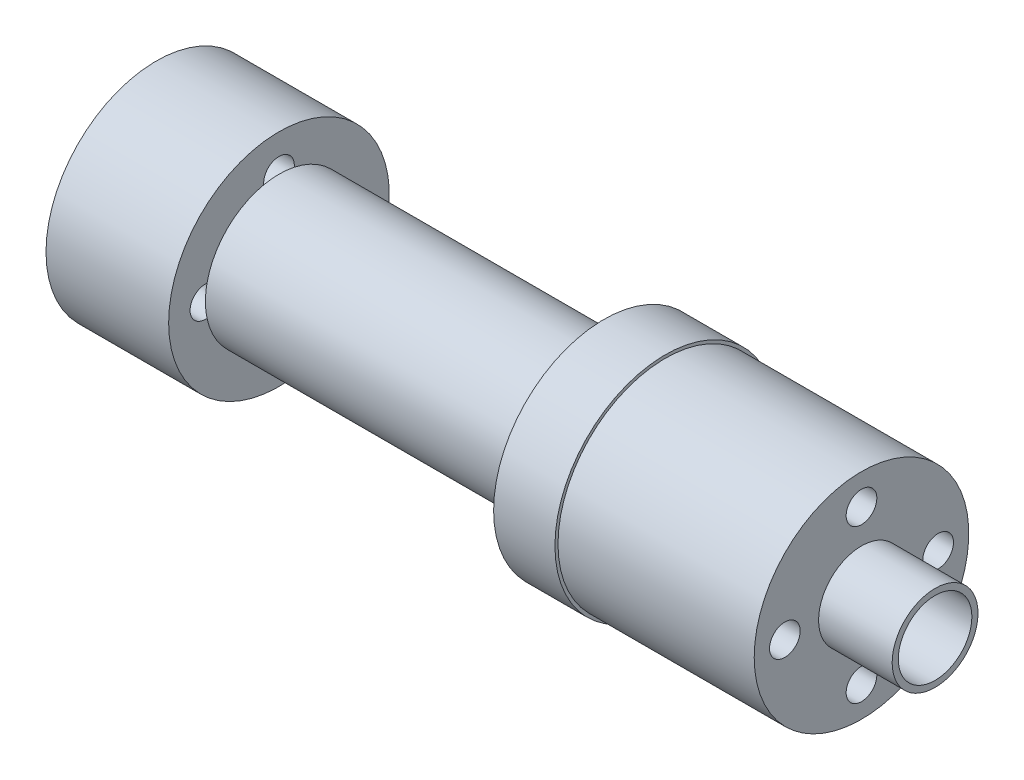
SolidWorks part; units mm, degrees
material "6061 合金"
ref_plane "前视基准面" through (0, 0, 0) normal (0, 0, 1) x (1, 0, 0)
ref_plane "上视基准面" through (0, 0, 0) normal (0, 1, 0) x (1, 0, 0)
ref_plane "右视基准面" through (0, 0, 0) normal (1, 0, 0) x (0, 0, -1)
sketch "草图1" plane through (0, 0, 0) normal (0, 0, 1) x (1, 0, 0)
  line L0 (0, 0) -> (40.4728, 0) construction
  line L1 (0, 9) -> (0, 3)
  line L2 (0, 3) -> (57.5, 3)
  line L3 (57.5, 3) -> (57.5, 8.75)
  line L4 (57.5, 8.75) -> (41.5, 8.75)
  line L5 (41.5, 8.75) -> (41.5, 9)
  line L7 (0, 9) -> (10, 9)
  line L8 (10, 9) -> (10, 6)
  line L9 (10, 6) -> (36.5, 6)
  line L10 (36.5, 6) -> (36.5, 9)
  line L11 (36.5, 9) -> (41.5, 9)
  point P14 (41.5, 8.875)
  dimension "D1" = 18
  dimension "D2" = 41.5
  dimension "D3" = 10
  dimension "D4" = 12
  dimension "D5" = 6
  dimension "D6" = 5
  dimension "D7" = 17.5
  dimension "D8" = 16
revolve "旋转1" add sketch "草图1" angle 360 about L0
sketch "草图3" plane through (0, 0, 0) normal (-1, 0, 0) x (0, 0, 1)
  circle A2 centre (0, 0) radius 6
  circle A3 centre (0, 0) radius 6 construction
  dimension "D1" = 3
hole_wizard "M3 螺纹孔1" positions "草图4" profile "草图5" tap size "M3" standard "GB" end condition up to next
sketch "草图4" plane through (0, 0, 0) normal (-1, 0, 0) x (0, 0, 1)
  circle A0 centre (0, 0) radius 6 construction
  point P0 (0, 6)
  point P4 (6, 0)
  point P6 (0, -6)
  point P8 (-6, 0)
sketch "草图5" plane through (0, 6, 0) normal (0, 1, 0) x (0, 0, 1)
  line L0 (0, 0) -> (0, 10)
  line L1 (0, 10) -> (1.25, 10)
  line L2 (1.25, 10) -> (1.25, 0)
  line L5 (1.25, 0) -> (0, 0)
  line L11 (0, -6.35) -> (0, 107.95) construction
  dimension "通孔螺纹孔钻头直径" = 2.5
  dimension "通孔螺纹孔钻头深度" = 10
cosmetic thread "孔螺蚊线1" parameters "D2"=3
cosmetic thread "孔螺蚊线2" parameters "D2"=3
cosmetic thread "孔螺蚊线3" parameters "D2"=3
cosmetic thread "孔螺蚊线4" parameters "D2"=3
sketch "草图6" plane through (57.5, 0, 0) normal (1, 0, 0) x (0, 0, -1)
  circle A2 centre (0, 0) radius 6.25
  circle A3 centre (0, 0) radius 6.25 construction
  dimension "D1" = 2.5
hole_wizard "M3 螺纹孔2" positions "草图7" profile "草图8" tap size "M3" standard "GB"
sketch "草图7" plane through (57.5, 0, 0) normal (1, 0, 0) x (0, 0, -1)
  circle A0 centre (0, 0) radius 6.25 construction
  point P0 (0, 6.25)
  point P4 (6.25, 0)
  point P6 (0, -6.25)
  point P8 (-6.25, 0)
sketch "草图8" plane through (57.5, 6.25, 0) normal (0, 1, 0) x (0, 0, -1)
  line L0 (0, 0) -> (0, 10.2511)
  line L1 (0, 10.2511) -> (1.25, 9.5)
  line L2 (1.25, 9.5) -> (1.25, 0)
  line L5 (1.25, 0) -> (0, 0)
  line L10 (0, 10.2511) -> (-1.25, 9.5) construction
  line L11 (0, -6.35) -> (0, 107.95) construction
  dimension "螺纹孔钻头直径" = 2.5
  dimension "螺纹孔钻头深度" = 9.5
  dimension "导头角度" = 118
cosmetic thread "孔螺蚊线5" parameters "D1"=8, "D2"=3
cosmetic thread "孔螺蚊线6" parameters "D1"=8, "D2"=3
cosmetic thread "孔螺蚊线7" parameters "D1"=8, "D2"=3
cosmetic thread "孔螺蚊线8" parameters "D1"=8, "D2"=3
sketch "草图9" plane through (57.5, 0, 0) normal (1, 0, 0) x (0, 0, -1)
  circle A0 centre (0, 0) radius 3.5
  circle A1 centre (0, 0) radius 3 construction
  circle A2 centre (0, 0) radius 3
  dimension "D1" = 7
extrude "凸台-拉伸1" add sketch "草图9" along normal blind 6
